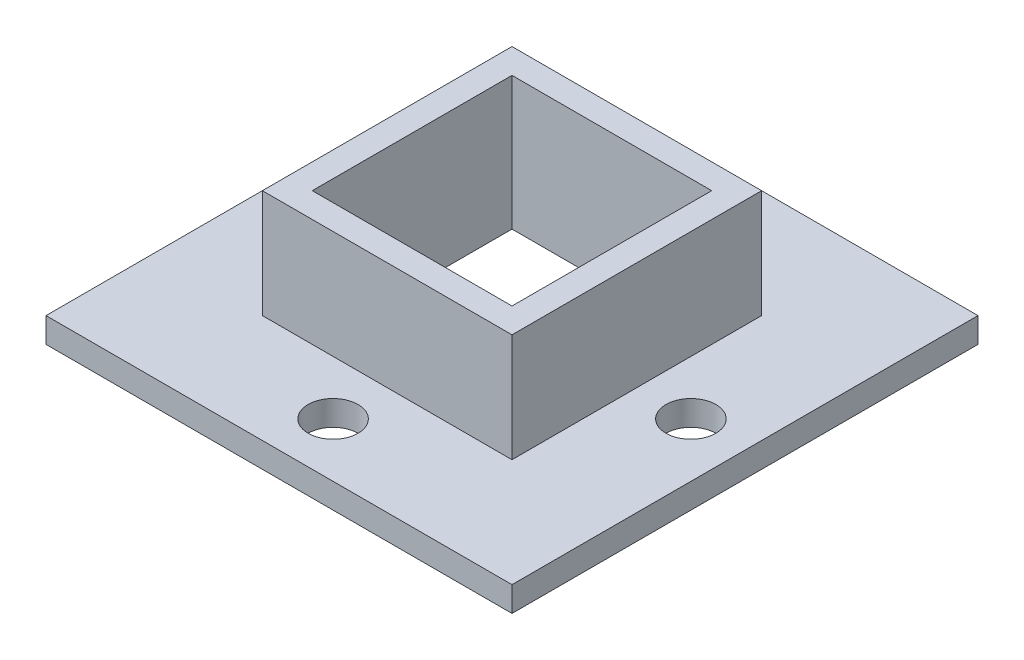
SolidWorks part; units mm, degrees
ref_plane "Alzado" through (0, 0, 0) normal (0, 0, 1) x (1, 0, 0)
ref_plane "Planta" through (0, 0, 0) normal (0, 1, 0) x (1, 0, 0)
ref_plane "Vista lateral" through (0, 0, 0) normal (1, 0, 0) x (0, 0, -1)
sketch "Croquis3" plane through (0, 0, 0) normal (0, 1, 0) x (1, 0, 0)
  line L0 (-88.9, 88.9) -> (88.9, 88.9)
  line L1 (-38.1, -38.1) -> (38.1, -38.1)
  line L2 (-38.1, -38.1) -> (-38.1, 38.1)
  line L3 (-38.1, 38.1) -> (38.1, 38.1)
  line L4 (38.1, -38.1) -> (38.1, 38.1)
  line L5 (-38.1, -38.1) -> (38.1, 38.1) construction
  line L6 (-38.1, 38.1) -> (38.1, -38.1) construction
  line L7 (88.9, -88.9) -> (88.9, 88.9)
  line L8 (-88.9, -88.9) -> (88.9, -88.9)
  line L9 (-88.9, -88.9) -> (-88.9, 88.9)
  point P0 (0, 0)
  dimension "D1" = 76.2
  dimension "D2" = 76.2
  dimension "D3" = 50.8
extrude "Saliente-Extruir2" add sketch "Croquis3" along normal blind 9.525
sketch "Croquis4" plane through (0, 9.525, 0) normal (0, 1, 0) x (1, 0, 0)
  line L0 (-47.625, 47.625) -> (-47.625, -47.625)
  line L1 (-38.1, 38.1) -> (38.1, 38.1)
  line L2 (-38.1, 38.1) -> (-38.1, -38.1)
  line L3 (-38.1, -38.1) -> (38.1, -38.1)
  line L4 (38.1, 38.1) -> (38.1, -38.1)
  line L5 (-47.625, -47.625) -> (47.625, -47.625)
  line L6 (47.625, 47.625) -> (47.625, -47.625)
  line L7 (-47.625, 47.625) -> (47.625, 47.625)
  dimension "D1" = 9.525
extrude "Saliente-Extruir3" add sketch "Croquis4" along normal blind 41.275
sketch "Croquis5" plane through (0, 9.525, 0) normal (0, 1, 0) x (1, 0, 0)
  line L0 (0, -47.625) -> (0, -88.9) construction
  line L1 (-47.625, -47.625) -> (47.625, -47.625) construction
  line L2 (-88.9, -88.9) -> (88.9, -88.9) construction
  line L3 (0, 0) -> (-38.1, 0) construction
  line L4 (-38.1, 38.1) -> (-38.1, -38.1) construction
  line L5 (0, 0) -> (-88.9, -88.9) construction
  line L6 (0, 0) -> (0, 38.1) construction
  line L7 (38.1, 38.1) -> (-38.1, 38.1) construction
  circle A0 centre (0, -68.2625) radius 9.525
  circle A1 centre (0, 68.2625) radius 9.525
  circle A2 centre (-68.2625, 0) radius 9.525
  circle A3 centre (68.2625, 0) radius 9.525
  dimension "D1" = 19.05
extrude "Cortar-Extruir1" cut sketch "Croquis5" against normal blind 12
